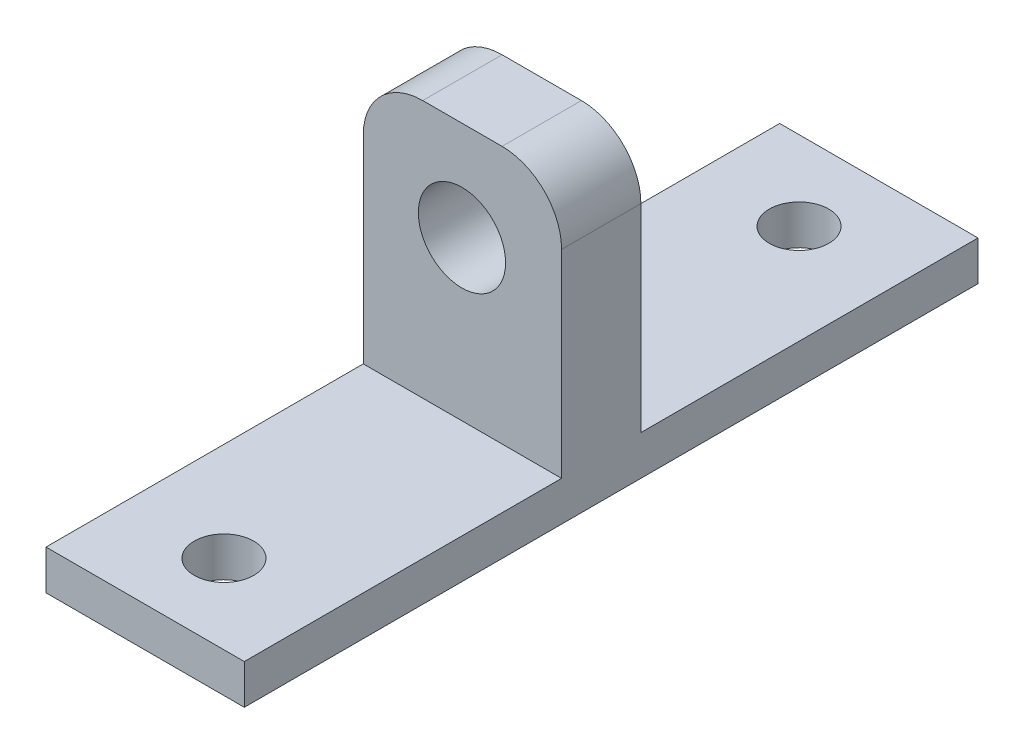
SolidWorks part; units mm, degrees
ref_plane "前视基准面" through (0, 0, 0) normal (0, 0, 1) x (1, 0, 0)
ref_plane "上视基准面" through (0, 0, 0) normal (0, 1, 0) x (1, 0, 0)
ref_plane "右视基准面" through (0, 0, 0) normal (1, 0, 0) x (0, 0, -1)
sketch "草图1" plane through (0, 0, 0) normal (0, 0, 1) x (1, 0, 0)
  line L0 (-4.9752, 0) -> (-4.9752, -8)
  line L1 (-4.9752, -8) -> (5.0248, -8)
  line L2 (5.0248, -8) -> (5.0248, 0)
  line L3 (-4.9752, 0) -> (-4.9752, 5)
  line L4 (-4.9752, 5) -> (5.0248, 5)
  line L5 (5.0248, 5) -> (5.0248, 0)
  circle A1 centre (0, 0) radius 2.2
  dimension "D1" = 10
  dimension "D3" = 4.4
  dimension "D2" = 8
  dimension "D4" = 5
extrude "凸台-拉伸1" add sketch "草图1" along normal blind 4
sketch "草图2" plane through (0, -8, 0) normal (0, -1, 0) x (1, 0, 0)
  line L0 (5.0248, 0) -> (5.0248, -18)
  line L1 (5.0248, 4) -> (5.0248, 0) construction
  line L2 (-4.9752, 0) -> (5.0248, 0) construction
  line L3 (5.0248, -18) -> (-4.9752, -18)
  line L4 (-4.9752, -18) -> (-4.9752, 21)
  line L5 (-4.9752, 21) -> (5.0248, 21)
  line L6 (5.0248, 21) -> (5.0248, 0)
  line L7 (0, 0) -> (0, -13) construction
  line L8 (-4.9752, 0) -> (5.0248, 0) construction
  circle A0 centre (0, -13) radius 1.5
  circle A1 centre (0, 16) radius 1.5
  dimension "D4" = 3
  dimension "D1" = 18
  dimension "D3" = 5
  dimension "D2" = 5
  dimension "D5" = 10
  dimension "D6" = 21
extrude "凸台-拉伸2" add sketch "草图2" along normal blind 2
fillet "圆角1" radius 3 2 edges at (5.0248, 5, 2) (-4.9752, 5, 2)
sketch "草图3" plane through (0, -10, 0) normal (0, -1, 0) x (1, 0, 0)
  line L0 (5.0248, -18) -> (5.0248, 21) construction
  line L1 (-4.9752, 21) -> (5.0248, 21)
  line L2 (-4.9752, 21) -> (-4.9752, 20)
  line L3 (-4.9752, 20) -> (5.0248, 20)
  line L4 (5.0248, 21) -> (5.0248, 20)
  line L6 (-4.9752, -18) -> (5.0248, -18)
  line L7 (-4.9752, -18) -> (-4.9752, -17)
  line L8 (-4.9752, -17) -> (5.0248, -17)
  line L9 (5.0248, -18) -> (5.0248, -17)
  dimension "D1" = 1
  dimension "D2" = 1
extrude "切除-拉伸1" cut sketch "草图3" against normal blind 10
